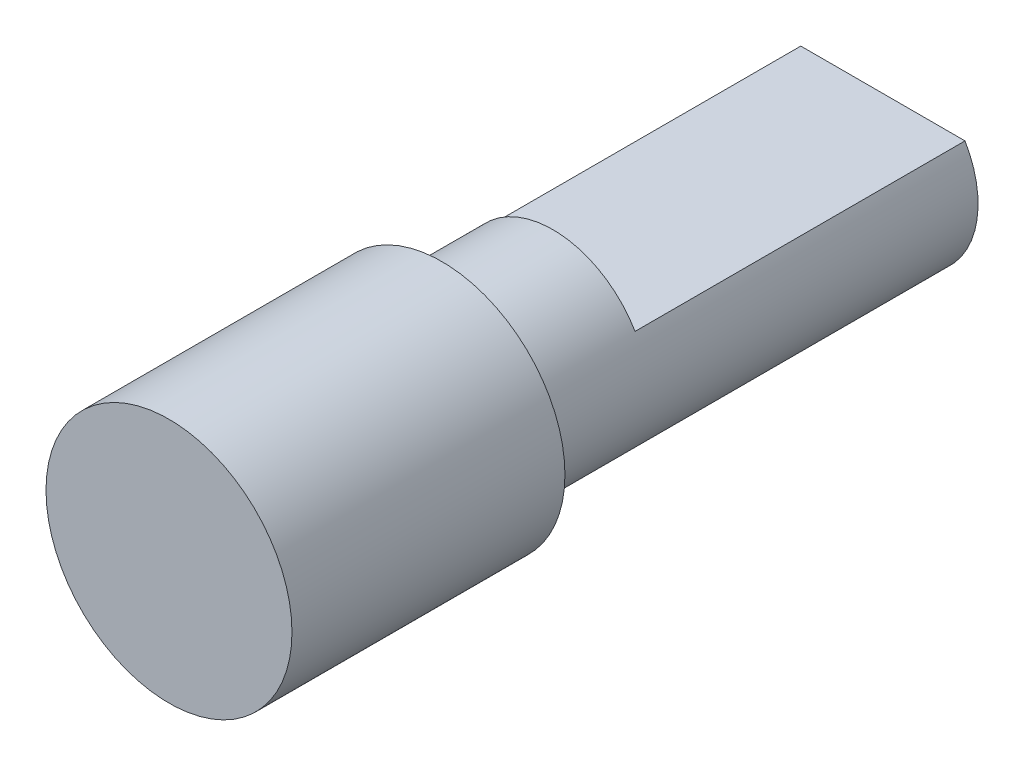
SolidWorks part; units mm, degrees
material "Custom Plastic"
ref_plane "X-Y Datum" through (0, 0, 0) normal (0, 0, 1) x (1, 0, 0)
ref_plane "X-Z Datum" through (0, 0, 0) normal (0, 1, 0) x (1, 0, 0)
ref_plane "Y-Z Datum" through (0, 0, 0) normal (1, 0, 0) x (0, 0, -1)
sketch "Sketch2" plane through (0, 0, 0) normal (0, 0, 1) x (1, 0, 0)
  circle A0 centre (0, 0) radius 4.1
  dimension "D1" = 8.2
extrude "Boss-Extrude1" add sketch "Sketch2" along normal blind 9.1
sketch "Sketch3" plane through (0, 0, 0) normal (0, 0, -1) x (-1, 0, 0)
  circle A0 centre (0, 0) radius 3.1725
  dimension "D1" = 6.345
extrude "Boss-Extrude2" add sketch "Sketch3" along normal blind 14.7
sketch "Sketch4" plane through (0, 0, -14.7) normal (0, 0, -1) x (-1, 0, 0)
  line L0 (-2.7377, 1.6031) -> (2.7377, 1.6031)
  circle A0 centre (0, 0) radius 3.1725 construction
  circle A1 centre (0, 0) radius 3.1725 construction
  arc A2 (-2.7377, 1.6031) -> (2.7377, 1.6031) centre (0, 0) ccw construction
  arc A3 (-2.7377, 1.6031) -> (2.7377, 1.6031) centre (0, 0) cw
  point P7 (0, -3.1725)
  dimension "D1" = 4.7756
extrude "Cut-Extrude1" cut sketch "Sketch4" against normal blind 11
